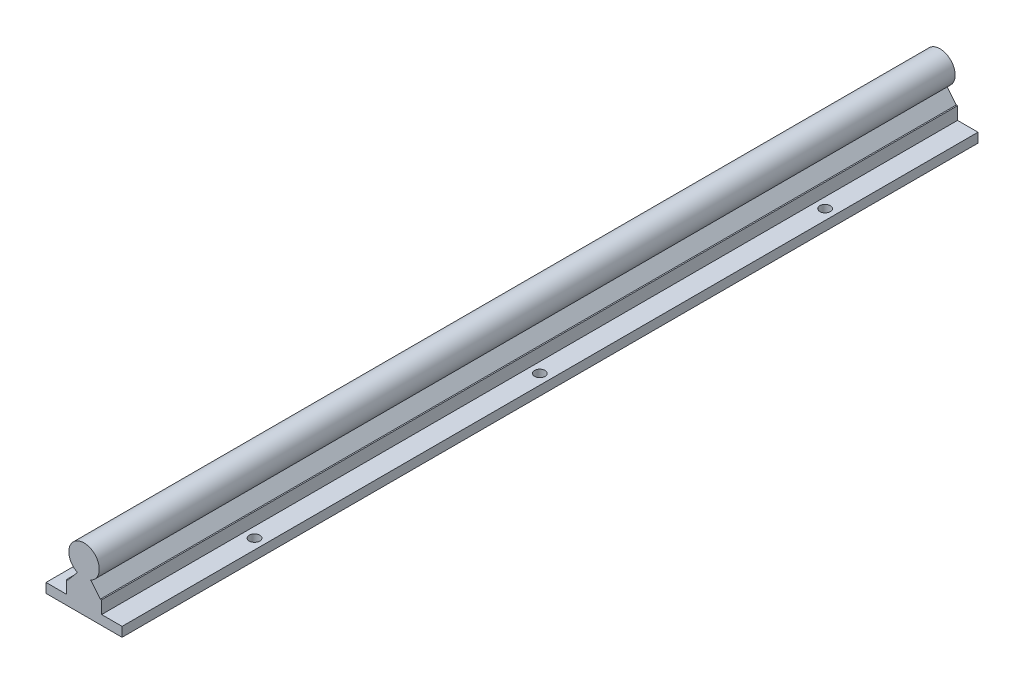
SolidWorks part; units mm, degrees
ref_plane "Front Plane" through (0, 0, 0) normal (0, 0, 1) x (1, 0, 0)
ref_plane "Top Plane" through (0, 0, 0) normal (0, 1, 0) x (1, 0, 0)
ref_plane "Right Plane" through (0, 0, 0) normal (1, 0, 0) x (0, 0, -1)
sketch "Sketch1" plane through (0, 0, 0) normal (0, 0, 1) x (1, 0, 0)
  line L0 (0, 25) -> (0, 0) construction
  line L1 (20, 0) -> (-20, 0)
  line L2 (-20, 0) -> (-20, 5)
  line L3 (-20, 5) -> (-9.25, 5)
  line L4 (-9.25, 5) -> (-9.25, 11.7)
  line L5 (-9.25, 11.7) -> (-8.6056, 11.7)
  line L6 (-8.6056, 11.7) -> (-3.4871, 17.8)
  line L7 (8.6056, 11.7) -> (3.4871, 17.8)
  line L8 (9.25, 11.7) -> (8.6056, 11.7)
  line L9 (9.25, 5) -> (9.25, 11.7)
  line L10 (20, 5) -> (9.25, 5)
  line L11 (20, 0) -> (20, 5)
  arc A0 (3.4871, 17.8) -> (-3.4871, 17.8) centre (0, 25) ccw
  dimension "D1" = 16
  dimension "D2" = 25
  dimension "D3" = 5
  dimension "D4" = 11.7
  dimension "D5" = 18.5
  dimension "D6" = 17.8
  dimension "D7" = 40
  dimension "D8" = 80
extrude "Boss-Extrude1" add sketch "Sketch1" along normal blind 450
sketch "Sketch2" plane through (0, 0, 0) normal (0, 1, 0) x (1, 0, 0)
  line L0 (-9.25, 0) -> (-20, 0) construction
  line L1 (0, 0) -> (0, -55.5123) construction
  line L2 (8, 0) -> (-8, 0) construction
  circle A0 centre (-14.625, -75) radius 2.75
  circle A1 centre (14.625, -75) radius 2.75
  circle A2 centre (-14.625, -225) radius 2.75
  circle A3 centre (14.625, -225) radius 2.75
  circle A4 centre (-14.625, -375) radius 2.75
  circle A5 centre (14.625, -375) radius 2.75
  point P4 (-14.625, 0)
  dimension "D1" = 75
  dimension "D2" = 5.5
  dimension "D3" = 3
extrude "Cut-Extrude1" cut sketch "Sketch2" along normal blind 450
